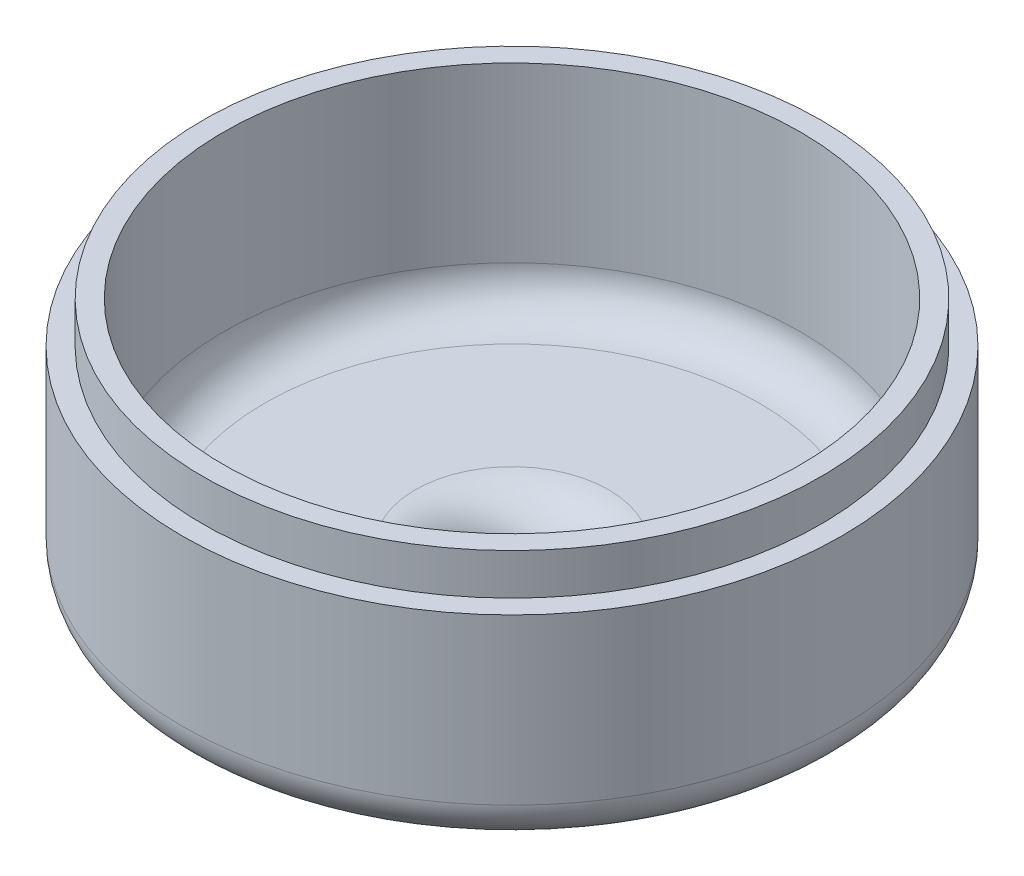
SolidWorks part; units mm, degrees
ref_plane "Front Plane" through (0, 0, 0) normal (0, 0, 1) x (1, 0, 0)
ref_plane "Top Plane" through (0, 0, 0) normal (0, 1, 0) x (1, 0, 0)
ref_plane "Right Plane" through (0, 0, 0) normal (1, 0, 0) x (0, 0, -1)
sketch "Sketch1" plane through (0, 0, 0) normal (0, 0, 1) x (1, 0, 0)
  line L0 (0, 0) -> (0, 37.1226) construction
  line L1 (-40, 5) -> (-40, -15)
  line L2 (-35, -20) -> (-16, -20)
  line L3 (-35, 10) -> (-35, -11)
  line L5 (-37.5, 10) -> (-35, 10)
  line L7 (-35, 10) -> (-35, -15) construction
  line L8 (-35, -15) -> (0, -15) construction
  line L9 (-40, 10) -> (-40, -20) construction
  line L10 (-40, -20) -> (0, -20) construction
  line L11 (-37.5, 10) -> (-37.5, 5)
  line L12 (-37.5, 5) -> (-40, 5)
  line L13 (-10, -26) -> (-10, -28.4863)
  line L15 (-10, -28.4863) -> (-5.75, -28.4863)
  line L17 (-30, -16) -> (-11.75, -16)
  line L18 (-5.75, -28.4863) -> (-5.75, -22)
  arc A0 (-35, -11) -> (-30, -16) centre (-30, -11) ccw
  arc A1 (-40, -15) -> (-35, -20) centre (-35, -15) ccw
  arc A2 (-10, -26) -> (-16, -20) centre (-16, -26) ccw
  arc A3 (-5.75, -22) -> (-11.75, -16) centre (-11.75, -22) ccw
  point P26 (-37.5, 7.5)
  dimension "D3" = 5
  dimension "D9" = 6
  dimension "D1" = 10
  dimension "D2" = 20
  dimension "D4" = 30
  dimension "D5" = 2.5
  dimension "D6" = 5
  dimension "D7" = 5.75
  dimension "D8" = 70
  dimension "D10" = 75
  dimension "D11" = 5
  dimension "D12" = 4
revolve "Revolve1" add sketch "Sketch1" angle 360 about L0
